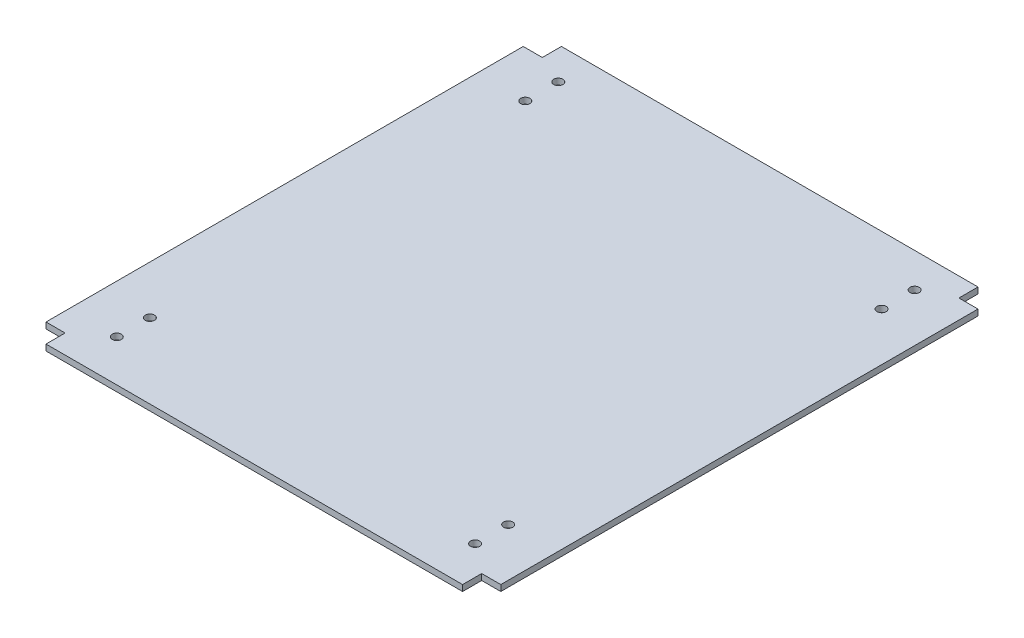
SolidWorks part; units mm, degrees
other "Markup1"
sketch "Sketch3" plane through (238.125, 6.35, 269.875) normal (0.6738, 0.6642, 0.3238) x (0.3784, 0.0662, -0.9233)
ref_plane "Front Plane" through (0, 0, 0) normal (0, 0, 1) x (1, 0, 0)
ref_plane "Top Plane" through (0, 0, 0) normal (0, 1, 0) x (1, 0, 0)
ref_plane "Right Plane" through (0, 0, 0) normal (1, 0, 0) x (0, 0, -1)
sketch "Sketch1" plane through (0, 0, 0) normal (0, 1, 0) x (1, 0, 0)
  line L0 (0, -269.875) -> (0, 269.875) construction
  line L1 (-218.125, 269.875) -> (218.125, 269.875)
  line L2 (-238.125, 249.875) -> (-238.125, -249.875)
  line L3 (-218.125, -269.875) -> (218.125, -269.875)
  line L4 (238.125, 249.875) -> (238.125, -249.875)
  line L5 (-218.125, 249.875) -> (218.125, -249.875) construction
  line L6 (-218.125, -249.875) -> (218.125, 249.875) construction
  line L9 (-238.125, -249.875) -> (-218.125, -249.875)
  line L10 (-218.125, -269.875) -> (-218.125, -249.875)
  line L11 (238.125, 0) -> (-238.125, 0) construction
  line L12 (-238.125, 249.875) -> (-218.125, 249.875)
  line L13 (-218.125, 269.875) -> (-218.125, 249.875)
  line L14 (218.125, 269.875) -> (218.125, 249.875)
  line L15 (238.125, 249.875) -> (218.125, 249.875)
  line L16 (238.125, -249.875) -> (218.125, -249.875)
  line L17 (218.125, -269.875) -> (218.125, -249.875)
  point P0 (0, 0)
  point P12 (0, 0)
  point P15 (0, 0)
  dimension "D1" = 476.25
  dimension "D2" = 539.75
  dimension "D3" = 20
  dimension "D4" = 20
extrude "Boss-Extrude4" add sketch "Sketch1" along normal blind 6.35
extrude "Cut-Extrude1" cut sketch "Sketch4" against normal blind 109.474
sketch "Sketch4" plane through (-189.7342, -3, -427.8454) normal (0, -1, 0) x (1, 0, 0)
  line L1 (29.6092, 209.0244) -> (-25.4143, 209.0244) construction
  line L4 (2.1092, 179.0244) -> (2.0975, 209.0244) construction
  circle A0 centre (2.1042, 226.3244) radius 4.826
  circle A1 centre (2.1042, 191.7244) radius 4.826
extrude "Cut-Extrude2" cut sketch "Sketch5" against normal blind 42.164
sketch "Sketch5" plane through (-189.7342, 0, -427.8454) normal (0, -1, 0) x (-1, 0, 0)
  circle A0 centre (-377.3744, -228.4453) radius 4.826
  circle A2 centre (-377.3744, -193.8453) radius 4.826
extrude "Cut-Extrude3" cut sketch "Sketch6" against normal blind 90.932
sketch "Sketch6" plane through (-189.7342, -3, -427.8454) normal (0, -1, 0) x (1, 0, 0)
  circle A0 centre (2.1042, 654.1017) radius 4.826
  circle A1 centre (2.1042, 619.5017) radius 4.826
extrude "Cut-Extrude4" cut sketch "Sketch7" against normal blind 90.932
sketch "Sketch7" plane through (-189.7342, -3, -427.8454) normal (0, -1, 0) x (1, 0, 0)
  circle A0 centre (377.3744, 654.1017) radius 4.826
  circle A1 centre (377.3744, 619.5017) radius 4.826
